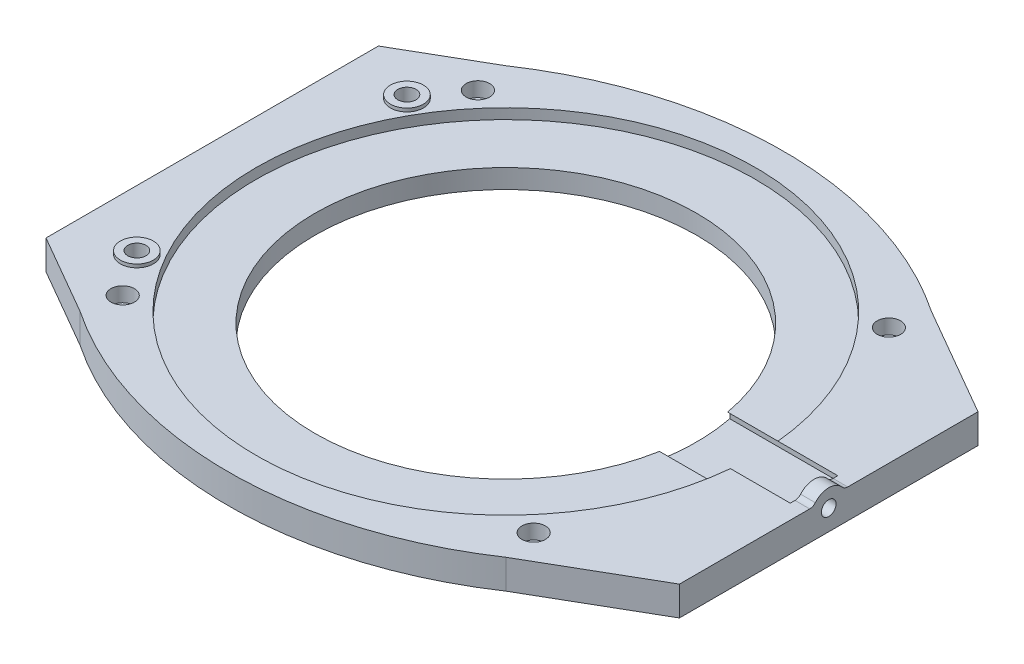
SolidWorks part; units mm, degrees
ref_plane "Front" through (0, 0, 0) normal (0, 0, 1) x (1, 0, 0)
ref_plane "Top" through (0, 0, 0) normal (0, 1, 0) x (1, 0, 0)
ref_plane "Right" through (0, 0, 0) normal (1, 0, 0) x (0, 0, -1)
sketch "Sketch1" plane through (0, 0, 0) normal (0, 1, 0) x (1, 0, 0)
  line L5 (-110, -105) -> (110, -105)
  line L6 (-110, -105) -> (-110, 105)
  line L7 (-110, 105) -> (110, 105)
  line L8 (110, -105) -> (110, 105)
  line L9 (-110, -105) -> (110, 105) construction
  line L10 (-110, 105) -> (110, -105) construction
  point P0 (0, 0)
  dimension "D1" = 210
  dimension "D2" = 220
extrude "Boss-Extrude1" add sketch "Sketch1" along normal blind 10
sketch "Sketch2" plane through (0, 10, 0) normal (0, 1, 0) x (1, 0, 0)
  circle A0 centre (0, 0) radius 65
  dimension "D1" = 130
extrude "Cut-Extrude1" cut sketch "Sketch2" against normal through all
sketch "Sketch3" plane through (0, 10, 0) normal (0, 1, 0) x (1, 0, 0)
  line L0 (-70, -60.5) -> (-70, 60.5) construction
  line L1 (-70, 60.5) -> (70, 60.5) construction
  line L2 (70, 60.5) -> (70, -60.5) construction
  line L3 (70, -60.5) -> (-70, -60.5) construction
  line L4 (-70, 0) -> (0, 0) construction
  line L5 (0, 0) -> (0, 60.5) construction
  circle A0 centre (70, 60.5) radius 2.25
  circle A1 centre (-70, 60.5) radius 2.25
  circle A2 centre (-70, -60.5) radius 2.25
  circle A3 centre (70, -60.5) radius 2.25
  dimension "D3" = 4.5
  dimension "D1" = 121
  dimension "D2" = 140
extrude "Cut-Extrude2" cut sketch "Sketch3" against normal through all
sketch "Sketch4" plane through (0, 10, 0) normal (0, 1, 0) x (1, 0, 0)
  circle A0 centre (0, 0) radius 85
  dimension "D1" = 170
extrude "Cut-Extrude3" cut sketch "Sketch4" against normal blind 3.5
sketch "Sketch5" plane through (0, 10, 0) normal (0, 1, 0) x (1, 0, 0)
  circle A0 centre (70, -60.5) radius 4
  circle A1 centre (-70, -60.5) radius 4
  circle A2 centre (-70, 60.5) radius 4
  circle A3 centre (70, 60.5) radius 4
  dimension "D1" = 8
extrude "Cut-Extrude4" cut sketch "Sketch5" against normal blind 5
sketch "Sketch6" plane through (0, 10, 0) normal (0, 1, 0) x (1, 0, 0)
  line L0 (-79.6743, -46) -> (0, 0) construction
  line L1 (0, 0) -> (-79.6743, 46) construction
  circle A0 centre (-79.6743, 46) radius 5.625
  circle A1 centre (-79.6743, -46) radius 5.625
  circle A2 centre (0, 0) radius 81 construction
  circle A3 centre (-79.6743, -46) radius 11 construction
  dimension "D1" = 162
  dimension "D2" = 11.25
  dimension "D4" = 22
  dimension "D3" = 60
extrude "Boss-Extrude2" add sketch "Sketch6" along normal blind 1.14 and the other way through all
sketch "Sketch8" plane through (0, 10, 0) normal (0, 1, 0) x (1, 0, 0)
  line L0 (0, 0) -> (72.5, -72.5) construction
  line L1 (0, 0) -> (72.5, 72.5) construction
  line L2 (0, 0) -> (-72.5, 72.5) construction
  line L3 (0, 0) -> (-72.5, -72.5) construction
  line L4 (-72.5, -72.5) -> (-110, -50.8494)
  line L5 (-110, 105) -> (-110, -105) construction
  line L7 (-110, 50.8494) -> (-72.5, 72.5)
  line L8 (-110, -50.8494) -> (-110, -105)
  line L9 (-110, -105) -> (110, -105)
  line L10 (110, -105) -> (110, -50.8494)
  line L11 (110, 105) -> (-110, 105)
  line L12 (-110, 105) -> (-110, 50.8494)
  line L13 (72.5, 72.5) -> (110, 50.8494)
  line L14 (72.5, -72.5) -> (110, -50.8494)
  line L15 (110, 50.8494) -> (110, 105)
  arc A1 (72.5, 72.5) -> (-72.5, 72.5) centre (0, -35.4062) ccw
  arc A2 (72.5, -72.5) -> (-72.5, -72.5) centre (0, 35.4062) cw
  dimension "D2" = 130
  dimension "D1" = 145
  dimension "D3" = 60
extrude "Cut-Extrude6" cut sketch "Sketch8" against normal through all
sketch "Sketch7" plane through (0, 0, 0) normal (1, 0, 0) x (0, 0, -1)
  line L0 (-12.5, 4) -> (12.5, 4)
  line L1 (12.5, 4) -> (12.5, 5.6)
  line L2 (12.5, 5.6) -> (8.1, 10)
  line L4 (8.1, 10) -> (-8.1, 10)
  line L5 (-8.1, 10) -> (-12.5, 5.6)
  line L6 (-12.5, 5.6) -> (-12.5, 4)
  line L7 (81, 10) -> (-81, 10) construction
  point P6 (0, 4)
  point P9 (0, 10)
  dimension "D1" = 6
  dimension "D2" = 45
  dimension "D3" = 1.6
  dimension "D4" = 25
extrude "Cut-Extrude5" cut sketch "Sketch7" along normal through all
sketch "Sketch9" plane through (0, 11.14, 0) normal (0, 1, 0) x (1, 0, 0)
  circle A0 centre (-79.6743, 46) radius 3.1
  circle A1 centre (-79.6743, -46) radius 3.1
  dimension "D1" = 6.2
extrude "Cut-Extrude7" cut sketch "Sketch9" against normal blind 11
sketch "Sketch10" plane through (0, 10, 0) normal (0, 1, 0) x (1, 0, 0)
  line L0 (110, 8.1) -> (110, 50.8494) construction
  line L1 (110, 23.4152) -> (105, 23.4152)
  line L2 (110, 23.4152) -> (110, -23.4152)
  line L3 (110, -23.4152) -> (105, -23.4152)
  line L4 (105, 23.4152) -> (105, -23.4152)
  line L5 (81, 0) -> (105, 0) construction
  circle A0 centre (0, 0) radius 81 construction
  point P6 (110, 0)
  dimension "D1" = 24
extrude "Boss-Extrude3" add sketch "Sketch10" against normal through all
sketch "Sketch11" plane through (110, 0, 0) normal (1, 0, 0) x (0, 0, -1)
  line L0 (0, 10) -> (0, 4) construction
  line L1 (81, 10) -> (-81, 10) construction
  line L2 (12.5, 4) -> (-12.5, 4) construction
  circle A0 centre (0, 7) radius 2.5
  dimension "D1" = 5
extrude "Cut-Extrude8" cut sketch "Sketch11" against normal up to surface (5 mm away) up to face at (105, 6.5333, 0)
sketch "Sketch12" plane through (0, 10, 0) normal (0, 1, 0) x (1, 0, 0)
  line L0 (-110, 50.8494) -> (-110, -50.8494) construction
  line L1 (-164.1092, 103.7133) -> (-100, 103.7133)
  line L2 (-164.1092, 103.7133) -> (-164.1092, -97.1552)
  line L3 (-164.1092, -97.1552) -> (-100, -97.1552)
  line L4 (-100, 103.7133) -> (-100, -97.1552)
  dimension "D1" = 10
extrude "Cut-Extrude9" cut sketch "Sketch12" against normal through all
sketch "Sketch13" plane through (-100, 0, 0) normal (-1, 0, 0) x (0, 0, 1)
  line L0 (-40, 5) -> (40, 5) construction
  line L1 (0, 0) -> (0, 10) construction
  line L2 (56.6229, 0) -> (-56.6229, 0) construction
  line L3 (81, 10) -> (-81, 10) construction
  circle A0 centre (-40, 5) radius 2.5
  circle A1 centre (40, 5) radius 2.5
  point P10 (0, 5)
  point P11 (0, 5)
  dimension "D2" = 5
  dimension "D1" = 80
extrude "Cut-Extrude10" cut sketch "Sketch13" against normal blind 12
sketch "Sketch14" plane through (110, 0, 0) normal (1, 0, 0) x (0, 0, -1)
  line L0 (-5.1962, 10) -> (5.1962, 10)
  line L1 (-50.8494, 10) -> (50.8494, 10) construction
  arc A0 (5.1962, 10) -> (-5.1962, 10) centre (0, 7) ccw
  dimension "D1" = 6
extrude "Boss-Extrude4" add sketch "Sketch14" against normal up to surface (5 mm away) up to face at (105, 7, 2.5)
fillet "Fillet1" radius 2.5 2 edges at (107.5, 10, -5.1962) (107.5, 10, 5.1962)
